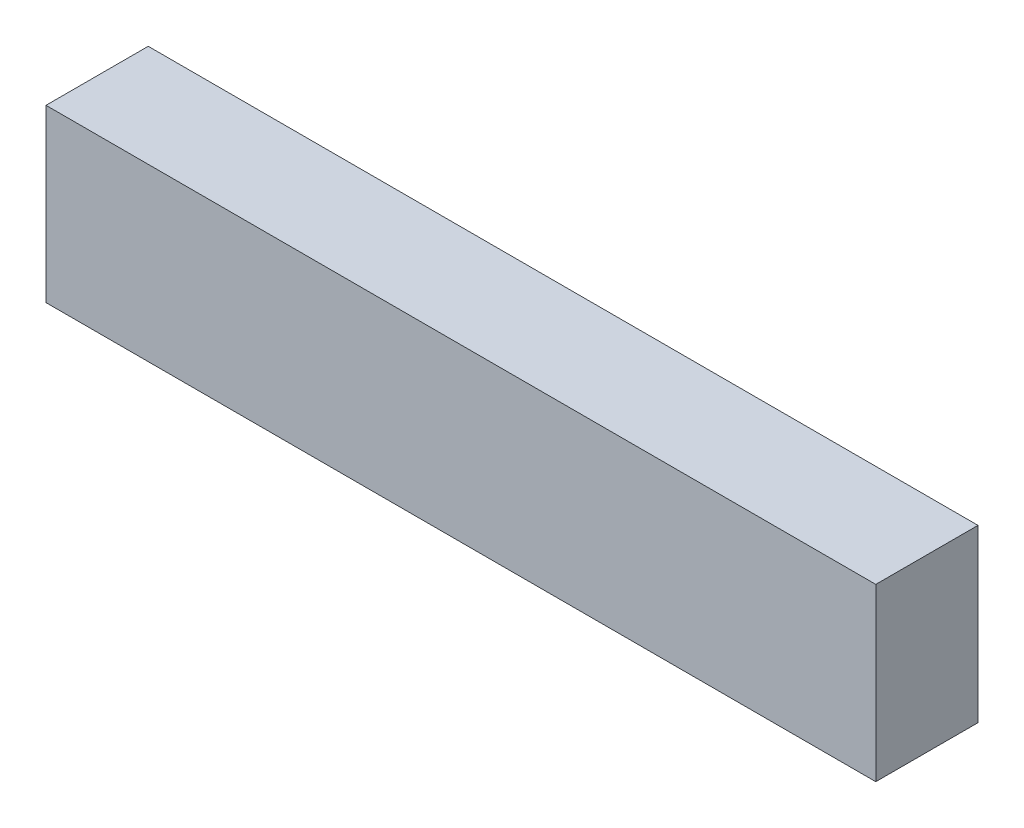
SolidWorks part; units mm, degrees
ref_plane "Front Plane" through (0, 0, 0) normal (0, 0, 1) x (1, 0, 0)
ref_plane "Top Plane" through (0, 0, 0) normal (0, 1, 0) x (1, 0, 0)
ref_plane "Right Plane" through (0, 0, 0) normal (1, 0, 0) x (0, 0, -1)
sketch "Sketch1" plane through (0, 0, 0) normal (0, 0, 1) x (1, 0, 0)
  line L0 (19.9845, -65.25) -> (79.2368, -65.25) construction
  line L1 (20.1845, -65.45) -> (79.0368, -65.45)
  line L2 (20.1845, -65.45) -> (20.1845, -77.5714)
  line L3 (20.1845, -77.5714) -> (79.0368, -77.5714)
  line L4 (79.0368, -65.45) -> (79.0368, -77.5714)
  line L5 (79.2368, -77.7714) -> (79.2368, -65.25) construction
  line L6 (19.9845, -77.7714) -> (79.2368, -77.7714) construction
  line L7 (19.9845, -77.7714) -> (19.9845, -65.25) construction
  dimension "D1" = 0.2
  dimension "D2" = 0.2
  dimension "D3" = 0.2
  dimension "D4" = 0.2
extrude "Boss-Extrude1" add sketch "Sketch1" along normal blind 7.25
shell "Shell1" thickness 0.5
equation "\"D2@Sketch1\"=\"D1@Sketch1\""
equation "\"D3@Sketch1\"=\"D1@Sketch1\""
equation "\"D4@Sketch1\"=\"D1@Sketch1\""
